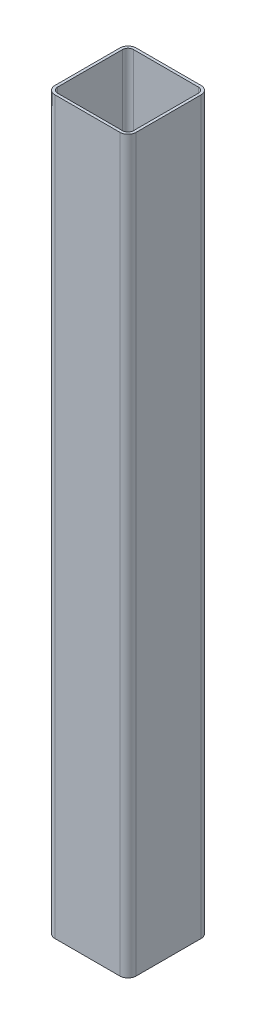
SolidWorks part; units mm, degrees
material "Plain Carbon Steel"
ref_plane "Front Plane" through (0, 0, 0) normal (0, 0, 1) x (1, 0, 0)
ref_plane "Top Plane" through (0, 0, 0) normal (0, 1, 0) x (1, 0, 0)
ref_plane "Right Plane" through (0, 0, 0) normal (1, 0, 0) x (0, 0, -1)
sketch "Sketch1" plane through (0, 0, 0) normal (0, 1, 0) x (1, 0, 0)
  line L1 (-24, -30) -> (24, -30)
  line L2 (-30, -24) -> (-30, 24)
  line L3 (-24, 30) -> (24, 30)
  line L4 (30, -24) -> (30, 24)
  line L5 (-30, -30) -> (30, 30) construction
  line L6 (-30, 30) -> (30, -30) construction
  arc A0 (30, -24) -> (24, -30) centre (24, -24) cw
  arc A1 (30, 24) -> (24, 30) centre (24, 24) ccw
  arc A2 (-24, 30) -> (-30, 24) centre (-24, 24) ccw
  arc A3 (-24, -30) -> (-30, -24) centre (-24, -24) cw
  point P0 (0, 0)
  dimension "D3" = 6
  dimension "D1" = 60
  dimension "D2" = 60
extrude "Boss-Extrude1" add sketch "Sketch1" along normal mid plane 540
shell "Shell1" thickness 2
sketch "Sketch2" [suppressed] plane through (0, 0, -30) normal (0, 0, -1) x (-1, 0, 0)
  line L1 (-15.5, 18.5021) -> (15.5, 18.5021)
  line L2 (-15.5, 18.5021) -> (-15.5, -12.4979)
  line L3 (-15.5, -12.4979) -> (15.5, -12.4979)
  line L4 (15.5, 18.5021) -> (15.5, -12.4979)
  line L5 (-15.5, 18.5021) -> (15.5, -12.4979) construction
  line L6 (-15.5, -12.4979) -> (15.5, 18.5021) construction
  line L7 (0, 33) -> (0, -33) construction
  line L9 (-27.4108, 3.0021) -> (27.4108, 3.0021) construction
  point P0 (0, 3.0021)
  dimension "D1" = 31
  dimension "D2" = 31
extrude "Cut-Extrude1" [suppressed] cut sketch "Sketch2" against normal through all
sketch "Sketch3" [suppressed] plane through (0, 0, -30) normal (0, 0, -1) x (-1, 0, 0)
  circle A0 centre (0, 0) radius 17.5
  dimension "D1" = 35
extrude "Cut-Extrude2" [suppressed] cut sketch "Sketch3" against normal through all
sketch "Sketch4" plane through (0, 0, -30) normal (0, 0, -1) x (-1, 0, 0)
  circle A0 centre (0, -235) radius 6 construction
  circle A1 centre (0, -185) radius 6 construction
  circle A2 centre (0, -235) radius 6
  circle A3 centre (0, -185) radius 6
extrude "Cut-Extrude3" [suppressed] cut sketch "Sketch4" against normal through all
